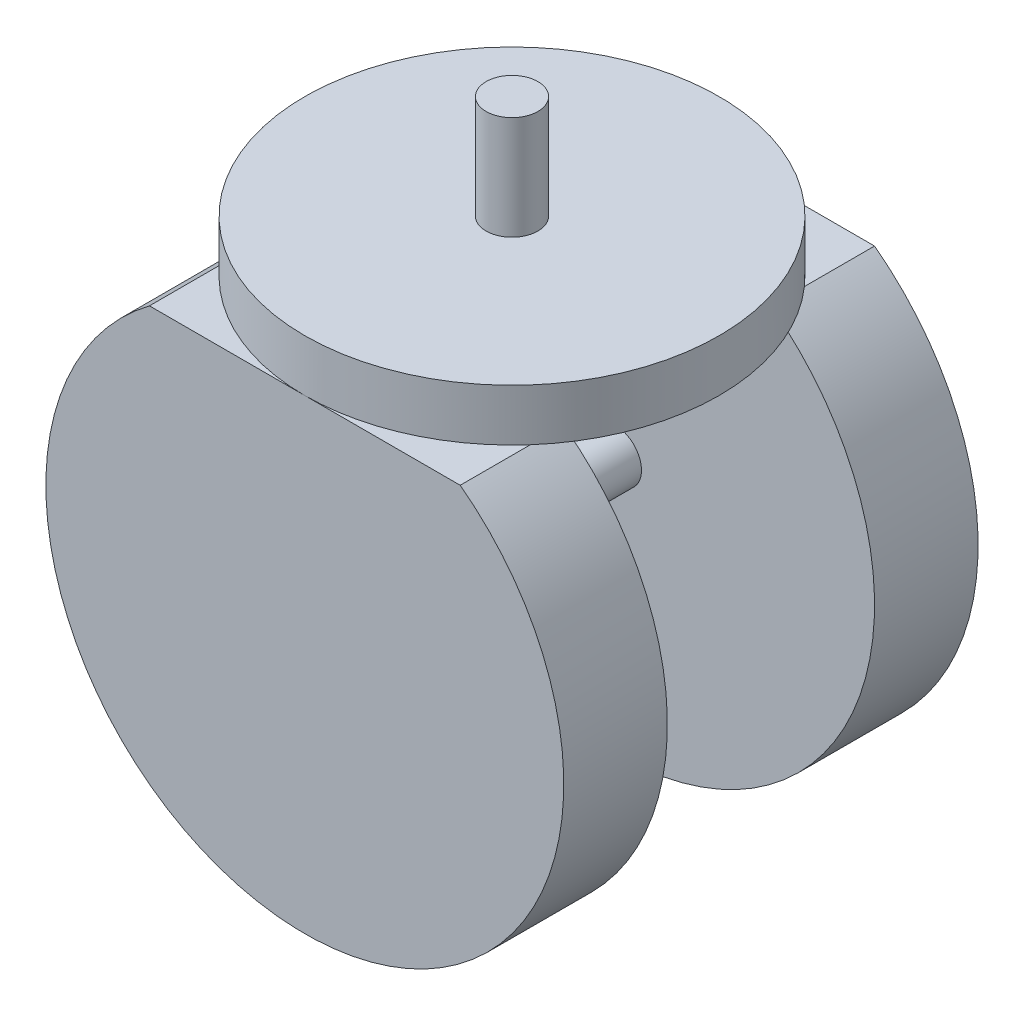
SolidWorks part; units mm, degrees
ref_plane "Front Plane" through (0, 0, 0) normal (0, 0, 1) x (1, 0, 0)
ref_plane "Top Plane" through (0, 0, 0) normal (0, 1, 0) x (1, 0, 0)
ref_plane "Right Plane" through (0, 0, 0) normal (1, 0, 0) x (0, 0, -1)
sketch "Sketch1" plane through (0, 0, 0) normal (0, 0, 1) x (1, 0, 0)
  circle A0 centre (0, 0) radius 63.5
  dimension "D1" = 127
extrude "Boss-Extrude2" add sketch "Sketch1" along normal blind 25.4
sketch "Sketch2" plane through (0, 0, 0) normal (0, 0, -1) x (-1, 0, 0)
  circle A0 centre (0, 0) radius 6.35
  dimension "D1" = 12.7
extrude "Boss-Extrude3" add sketch "Sketch2" along normal blind 50.8
sketch "Sketch3" plane through (0, 0, -50.8) normal (0, 0, -1) x (-1, 0, 0)
  circle A0 centre (0, 0) radius 63.5
  dimension "D1" = 127
extrude "Boss-Extrude4" add sketch "Sketch3" along normal blind 25.4
sketch "Sketch4" plane through (0, 0, 0) normal (0, 1, 0) x (1, 0, 0)
  line L0 (0, 50.8) -> (0, 0) construction
  line L1 (-6.35, 50.8) -> (6.35, 50.8) construction
  line L2 (63.5, 76.2) -> (-63.5, 76.2) construction
  line L3 (-63.5, -25.4) -> (63.5, -25.4)
  line L4 (-63.5, -25.4) -> (-63.5, 76.2)
  line L5 (-63.5, 76.2) -> (63.5, 76.2)
  line L6 (63.5, -25.4) -> (63.5, 76.2)
  line L7 (-63.5, -25.4) -> (63.5, 76.2) construction
  line L8 (-63.5, 76.2) -> (63.5, -25.4) construction
  point P5 (0, 25.4)
  dimension "D1" = 127
extrude "Cut-Extrude2" cut sketch "Sketch4" along normal blind 76.2 from offset 50.8
sketch "Sketch5" plane through (0, 50.8, 0) normal (0, 1, 0) x (1, 0, 0)
  line L0 (38.1, 76.2) -> (-38.1, 76.2) construction
  line L1 (-38.1, -25.4) -> (38.1, -25.4) construction
  circle A0 centre (0, 25.4) radius 50.8
  point P6 (0, 0)
extrude "Boss-Extrude5" add sketch "Sketch5" along normal blind 12.7
sketch "Sketch6" plane through (0, 63.5, 0) normal (0, 1, 0) x (1, 0, 0)
  circle A0 centre (0, 25.4) radius 6.35
  circle A1 centre (0, 25.4) radius 50.8 construction
  dimension "D1" = 12.7
extrude "Boss-Extrude6" add sketch "Sketch6" along normal blind 25.4
